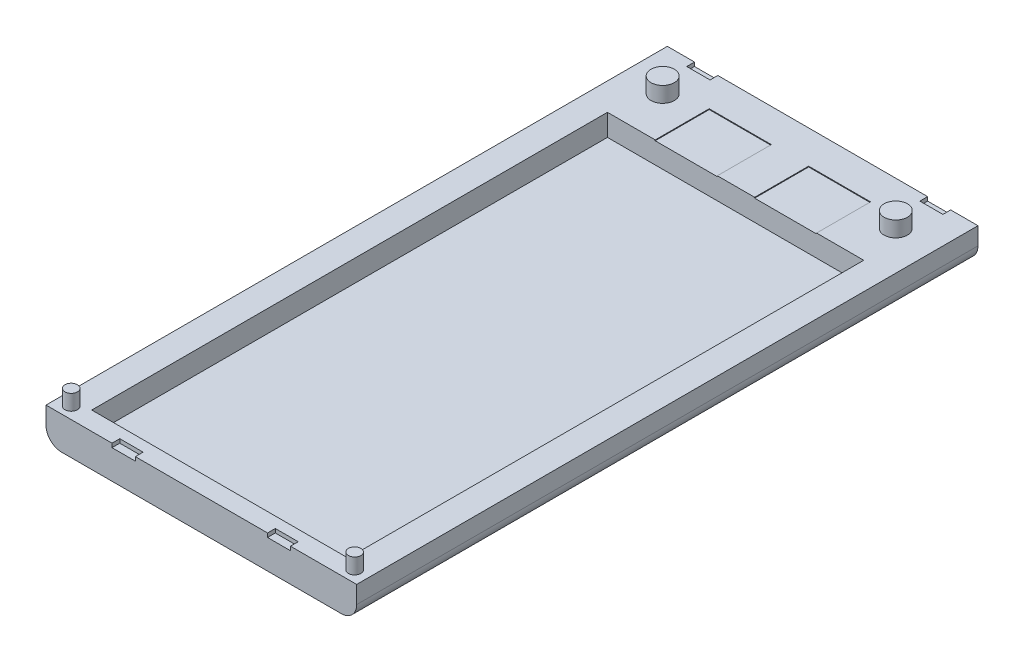
SolidWorks part; units mm, degrees
ref_plane "Front" through (0, 0, 0) normal (0, 0, 1) x (1, 0, 0)
ref_plane "Top" through (0, 0, 0) normal (0, 1, 0) x (1, 0, 0)
ref_plane "Right" through (0, 0, 0) normal (1, 0, 0) x (0, 0, -1)
sketch "Sketch2" plane through (0, 0, 0) normal (0, 1, 0) x (1, 0, 0)
  line L1 (-20, -40) -> (20, -40)
  line L2 (-20, -40) -> (-20, 40)
  line L3 (-20, 40) -> (20, 40)
  line L4 (20, -40) -> (20, 40)
  line L5 (-20, -40) -> (20, 40) construction
  line L6 (-20, 40) -> (20, -40) construction
  point P0 (0, 0)
  point P5 (0, 0)
  dimension "D1" = 40
  dimension "D2" = 80
extrude "Boss-Extrude2" add sketch "Sketch2" along normal blind 4.25
sketch3d "3DSketch2"
  line L0 (-20, 4.25, 40) -> (20, 4.25, 40) construction
  line L1 (0, 4.25, 40.1053) -> (0, 4.25, 37.6116) construction
  line L3 (-16.5, 4.25, 37.6116) -> (-16.5, 4.25, -28.7884)
  line L4 (-16.5, 4.25, 37.6116) -> (16.5, 4.25, 37.6116)
  line L5 (16.5, 4.25, 37.6116) -> (16.5, 4.25, -28.7884)
  line L6 (-16.5, 4.25, -28.7884) -> (16.5, 4.25, -28.7884)
  point P6 (-0.0432, 4.25, 37.5063)
  point P9 (0, 4.25, 37.6116)
  dimension "D1" = 33
  dimension "D2" = 66.4
extrude "Cut-Extrude3" cut sketch "3DSketch2" along direction (0, -1, 0) on the side of the normal blind 2.8
sketch3d "3DSketch3"
  line L3 (-2.3478, 4.25, -28.7884) -> (-10.3486, 4.25, -28.7884)
  line L4 (-2.3478, 4.25, -28.7884) -> (-2.3478, 4.25, -35.7397)
  line L5 (-2.3478, 4.25, -35.7397) -> (-10.3486, 4.25, -35.7397)
  line L6 (-10.3486, 4.25, -28.7884) -> (-10.3486, 4.25, -35.7397)
  line L7 (2.4522, 4.25, -28.7884) -> (10.4269, 4.25, -28.7884)
  line L8 (2.4522, 4.25, -28.7884) -> (2.4522, 4.25, -35.7397)
  line L9 (2.4522, 4.25, -35.7397) -> (10.4269, 4.25, -35.7397)
  line L10 (10.4269, 4.25, -28.7884) -> (10.4269, 4.25, -35.7397)
  point P5 (0.0522, 4.25, -28.7884)
extrude "Cut-Extrude4" cut sketch "3DSketch3" along direction (0, -1, 0) on the side against the normal blind 0.1
sketch3d "3DSketch4"
  line L0 (-20, 4.25, -40) -> (-10, 4.25, -40) construction
  line L1 (-15, 4.25, -40) -> (-15, 4.25, -34.4) construction
  line L2 (20.013, 4.25, -40) -> (10.013, 4.25, -40) construction
  line L3 (15.013, 4.25, -40) -> (15.013, 4.25, -34.4) construction
  circle A0 centre (-15, 4.25, -34.4) radius 1.5
  circle A1 centre (15.013, 4.25, -34.4) radius 1.5
  point P5 (-15, 5.75, -34.4)
  point P11 (15.013, 5.75, -34.4)
extrude "Boss-Extrude3" add sketch "3DSketch4" along direction (0, -1, 0) on the side against the normal blind 2
sketch3d "3DSketch5"
  line L0 (-20, 4.25, 40) -> (-16.5, 4.25, 40) construction
  line L1 (-18.25, 4.25, 40) -> (-18.25, 4.25, 38.508) construction
  line L2 (20.0004, 4.25, 40) -> (16.5004, 4.25, 40) construction
  line L3 (18.2504, 4.25, 40) -> (18.2504, 4.25, 38.508) construction
  circle A0 centre (-18.25, 4.25, 38.508) radius 0.8
  circle A1 centre (18.2504, 4.25, 38.508) radius 0.8
  point P5 (-18.25, 5.05, 38.508)
  point P11 (18.2504, 5.05, 38.508)
extrude "Boss-Extrude4" add sketch "3DSketch5" along direction (0, -1, 0) on the side against the normal blind 2
fillet "Fillet1" radius 2 2 edges at (20, 0, 0) (-20, 0, 0)
sketch3d "3DSketch6"
  line L0 (0, 4.25, 40) -> (-20, 4.25, 40) construction
  line L1 (-10, 4.25, 40) -> (-10, 3.2437, 40) construction
  line L2 (-10, 4.25, 40) -> (-10, 3.7469, 40) construction
  line L3 (0, 4.25, 40) -> (20, 4.25, 40) construction
  line L4 (-11.5029, 3.7469, 40) -> (-8.4971, 3.7469, 40)
  line L5 (-11.5029, 3.7469, 40) -> (-11.5029, 4.25, 40)
  line L6 (-11.5029, 4.25, 40) -> (-8.4971, 4.25, 40)
  line L7 (-8.4971, 3.7469, 40) -> (-8.4971, 4.25, 40)
  line L8 (-11.5029, 3.7469, 40) -> (-8.4971, 4.25, 40) construction
  line L9 (-11.5029, 4.25, 40) -> (-8.4971, 3.7469, 40) construction
  line L10 (10, 4.25, 40) -> (10, 3.7469, 40) construction
  line L12 (8.5236, 3.7469, 40) -> (11.4764, 3.7469, 40)
  line L13 (8.5236, 3.7469, 40) -> (8.5236, 4.25, 40)
  line L14 (8.5236, 4.25, 40) -> (11.4764, 4.25, 40)
  line L15 (11.4764, 3.7469, 40) -> (11.4764, 4.25, 40)
  line L16 (8.5236, 3.7469, 40) -> (11.4764, 4.25, 40) construction
  line L17 (8.5236, 4.25, 40) -> (11.4764, 3.7469, 40) construction
  point P5 (-10, 3.9984, 40)
  point P13 (10, 3.9984, 40)
  dimension "D1" = 1.0063
extrude "Cut-Extrude5" cut sketch "3DSketch6" along direction (0, 0, 1) on the side against the normal blind 1
sketch "Sketch4" plane through (0, 0, -40) normal (0, 0, -1) x (-1, 0, 0)
  line L0 (-15, 4.25) -> (-15, 3.75) construction
  line L1 (-20, 4.25) -> (-10, 4.25) construction
  line L2 (-10, 4.25) -> (-20, 4.25) construction
  line L3 (0, 4.25) -> (20, 4.25) construction
  line L4 (-16.4815, 3.75) -> (-13.5185, 3.75)
  line L5 (-16.4815, 3.75) -> (-16.4815, 4.25)
  line L6 (-16.4815, 4.25) -> (-13.5185, 4.25)
  line L7 (-13.5185, 3.75) -> (-13.5185, 4.25)
  line L8 (-16.4815, 3.75) -> (-13.5185, 4.25) construction
  line L9 (-16.4815, 4.25) -> (-13.5185, 3.75) construction
  line L10 (10, 4.25) -> (20, 4.25) construction
  line L11 (15, 4.25) -> (15, 3.75) construction
  line L13 (13.5006, 3.75) -> (16.4994, 3.75)
  line L14 (13.5006, 3.75) -> (13.5006, 4.25)
  line L15 (13.5006, 4.25) -> (16.4994, 4.25)
  line L16 (16.4994, 3.75) -> (16.4994, 4.25)
  line L17 (13.5006, 3.75) -> (16.4994, 4.25) construction
  line L18 (13.5006, 4.25) -> (16.4994, 3.75) construction
  point P7 (-15, 4)
  point P14 (15, 4)
extrude "Cut-Extrude6" cut sketch "Sketch4" against normal blind 1
sketch3d "3DSketch7" plane through (0, 0, 0) normal (0, 0, 1) x (1, 0, 0)
sketch "Sketch5" plane through (0, 0, 0) normal (0, -1, 0) x (-1, 0, 0)
  text T0 "Volta Cell" font "Century Gothic" height in points 12
extrude "Cut-Extrude7" cut sketch "Sketch5" against normal blind 0.5
